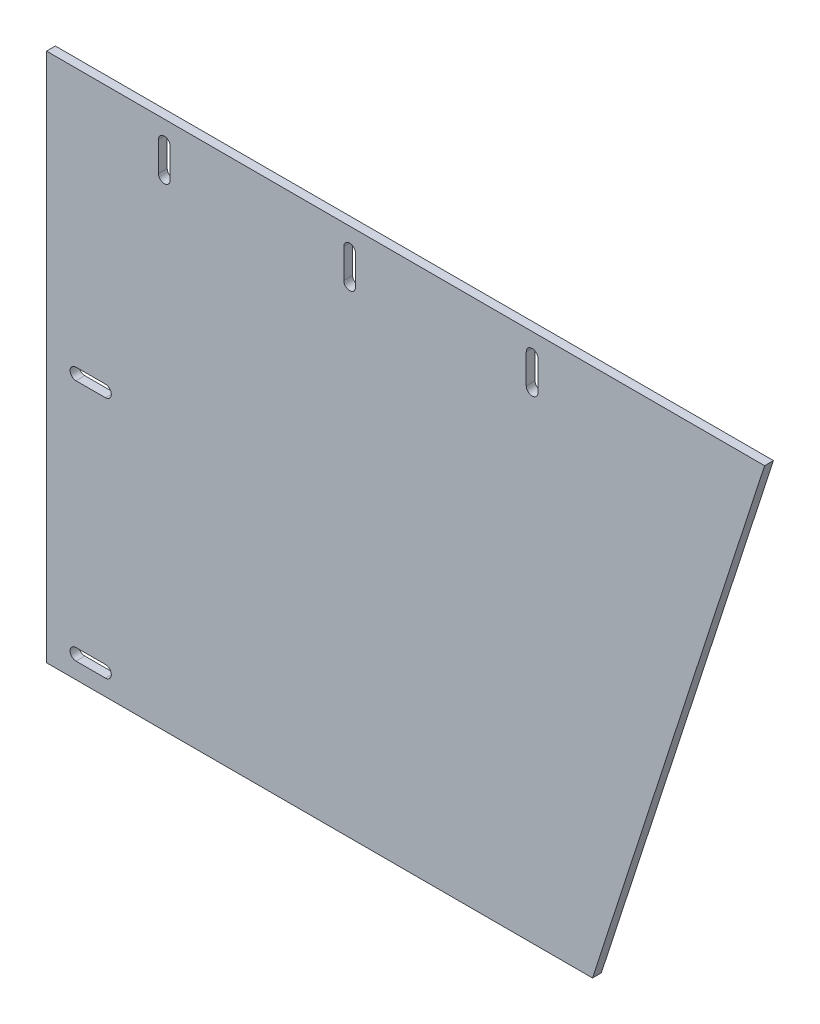
SolidWorks part; units mm, degrees
ref_plane "Front Plane" through (0, 0, 0) normal (0, 0, 1) x (1, 0, 0)
ref_plane "Top Plane" through (0, 0, 0) normal (0, 1, 0) x (1, 0, 0)
ref_plane "Right Plane" through (0, 0, 0) normal (1, 0, 0) x (0, 0, -1)
sketch "Sketch1" plane through (0, 0, 0) normal (0, 0, 1) x (1, 0, 0)
  line L1 (-122, 90) -> (122, 90)
  line L2 (-122, 90) -> (-122, -90)
  line L3 (-122, -90) -> (122, -90)
  line L4 (122, 90) -> (122, -90)
  line L5 (-122, 90) -> (122, -90) construction
  line L6 (-122, -90) -> (122, 90) construction
  point P0 (0, 0)
  dimension "D1" = 180
  dimension "D2" = 244
extrude "Boss-Extrude1" add sketch "Sketch1" along normal blind 3
sketch "Sketch2" plane through (0, 0, 3) normal (0, 0, 1) x (1, 0, 0)
  line L0 (122, 90) -> (63.5145, -90)
  line L1 (-122, -90) -> (122, -90) construction
  line L2 (63.5145, -90) -> (122, -90)
  line L3 (122, -90) -> (122, 90)
  dimension "D1" = 72
extrude "Cut-Extrude1" cut sketch "Sketch2" against normal blind 3
sketch "Sketch3" plane through (0, 0, 3) normal (0, 0, 1) x (1, 0, 0)
  line L0 (-82, 83) -> (-82, 73) construction
  line L1 (-80, 83) -> (-80, 73)
  line L2 (-84, 83) -> (-84, 73)
  line L3 (-19, 83) -> (-19, 73) construction
  line L4 (-17, 83) -> (-17, 73)
  line L5 (-21, 83) -> (-21, 73)
  line L6 (43, 83) -> (43, 73) construction
  line L7 (45, 83) -> (45, 73)
  line L8 (41, 83) -> (41, 73)
  line L9 (122, 90) -> (-122, 90) construction
  line L10 (-122, 90) -> (-122, -90) construction
  line L11 (-112, 0) -> (-102, 0) construction
  line L12 (-112, 2) -> (-102, 2)
  line L13 (-112, -2) -> (-102, -2)
  line L14 (-112, -82.5) -> (-102, -82.5) construction
  line L15 (-112, -80.5) -> (-102, -80.5)
  line L16 (-112, -84.5) -> (-102, -84.5)
  line L17 (-122, -90) -> (63.5145, -90) construction
  arc A0 (-80, 83) -> (-84, 83) centre (-82, 83) ccw
  arc A1 (-84, 73) -> (-80, 73) centre (-82, 73) ccw
  arc A2 (-17, 83) -> (-21, 83) centre (-19, 83) ccw
  arc A3 (-21, 73) -> (-17, 73) centre (-19, 73) ccw
  arc A4 (45, 83) -> (41, 83) centre (43, 83) ccw
  arc A5 (41, 73) -> (45, 73) centre (43, 73) ccw
  arc A6 (-112, 2) -> (-112, -2) centre (-112, 0) ccw
  arc A7 (-102, -2) -> (-102, 2) centre (-102, 0) ccw
  arc A8 (-112, -80.5) -> (-112, -84.5) centre (-112, -82.5) ccw
  arc A9 (-102, -84.5) -> (-102, -80.5) centre (-102, -82.5) ccw
  point P2 (-82, 78)
  point P7 (-19, 78)
  point P14 (43, 78)
  point P28 (-107, 0)
  point P35 (-107, -82.5)
  dimension "D1" = 2
  dimension "D2" = 2
  dimension "D3" = 2
  dimension "D13" = 2
  dimension "D18" = 2
  dimension "D4" = 10
  dimension "D5" = 10
  dimension "D6" = 10
  dimension "D7" = 7
  dimension "D8" = 7
  dimension "D9" = 7
  dimension "D10" = 40
  dimension "D11" = 79
  dimension "D12" = 103
  dimension "D14" = 10
  dimension "D15" = 10
  dimension "D16" = 90
  dimension "D17" = 10
  dimension "D19" = 10
  dimension "D20" = 7.5
extrude "Cut-Extrude2" cut sketch "Sketch3" against normal blind 3
